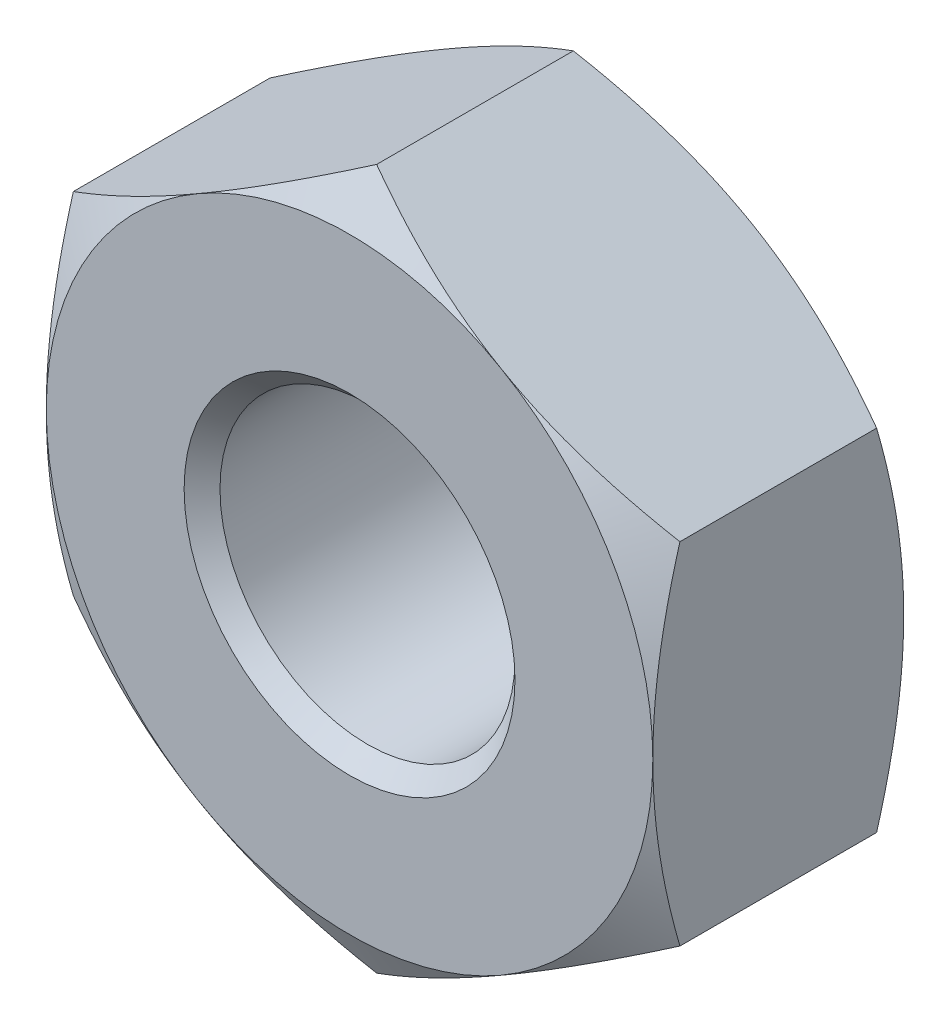
SolidWorks part; units mm, degrees
ref_plane "Front Plane" through (0, 0, 0) normal (0, 0, 1) x (1, 0, 0)
ref_plane "Top Plane" through (0, 0, 0) normal (0, 1, 0) x (1, 0, 0)
ref_plane "Right Plane" through (0, 0, 0) normal (1, 0, 0) x (0, 0, -1)
sketch "Sketch1" plane through (0, 0, 0) normal (0, 0, 1) x (1, 0, 0)
  line L1 (0, 3.1754) -> (-2.75, 1.5877)
  line L2 (-2.75, 1.5877) -> (-2.75, -1.5877)
  line L3 (-2.75, -1.5877) -> (0, -3.1754)
  line L4 (0, -3.1754) -> (2.75, -1.5877)
  line L5 (2.75, -1.5877) -> (2.75, 1.5877)
  line L6 (2.75, 1.5877) -> (0, 3.1754)
  circle A0 centre (0, 0) radius 2.75 construction
  circle A1 centre (0, 0) radius 1.3375
  dimension "D1" = 2.675
  dimension "D2" = 5.5
extrude "Boss-Extrude1" add sketch "Sketch1" along normal blind 2.275
sketch "Sketch2" plane through (0, 0, 0) normal (1, 0, 0) x (0, 0, -1)
  line L0 (0, 0) -> (-2.275, 0) construction
  line L1 (-2.275, -1.5877) -> (-2.275, 1.5877) construction
  line L2 (-2.275, 1.3375) -> (-2.275, 1.5)
  line L3 (-2.275, 1.5) -> (-2.1125, 1.3375)
  line L4 (-2.1125, 1.3375) -> (-2.275, 1.3375)
  line L5 (-2.275, 3.1754) -> (-2.275, 2.75)
  line L6 (-2.275, 2.75) -> (-2.0294, 3.1754)
  line L7 (-2.275, 3.1754) -> (0, 3.1754) construction
  line L8 (-2.0294, 3.1754) -> (-2.275, 3.1754)
  line L9 (-1.1375, 0) -> (-1.1375, 3.1754) construction
  line L10 (-0.2456, 3.1754) -> (0, 3.1754)
  line L11 (0, 2.75) -> (-0.2456, 3.1754)
  line L12 (0, 3.1754) -> (0, 2.75)
  line L13 (-0.1625, 1.3375) -> (0, 1.3375)
  line L14 (0, 1.5) -> (-0.1625, 1.3375)
  line L15 (0, 1.3375) -> (0, 1.5)
  dimension "D1" = 30
  dimension "D2" = 5.5
  dimension "D3" = 3
  dimension "D4" = 45
revolve "Cut-Revolve1" cut sketch "Sketch2" angle 360 about L0
